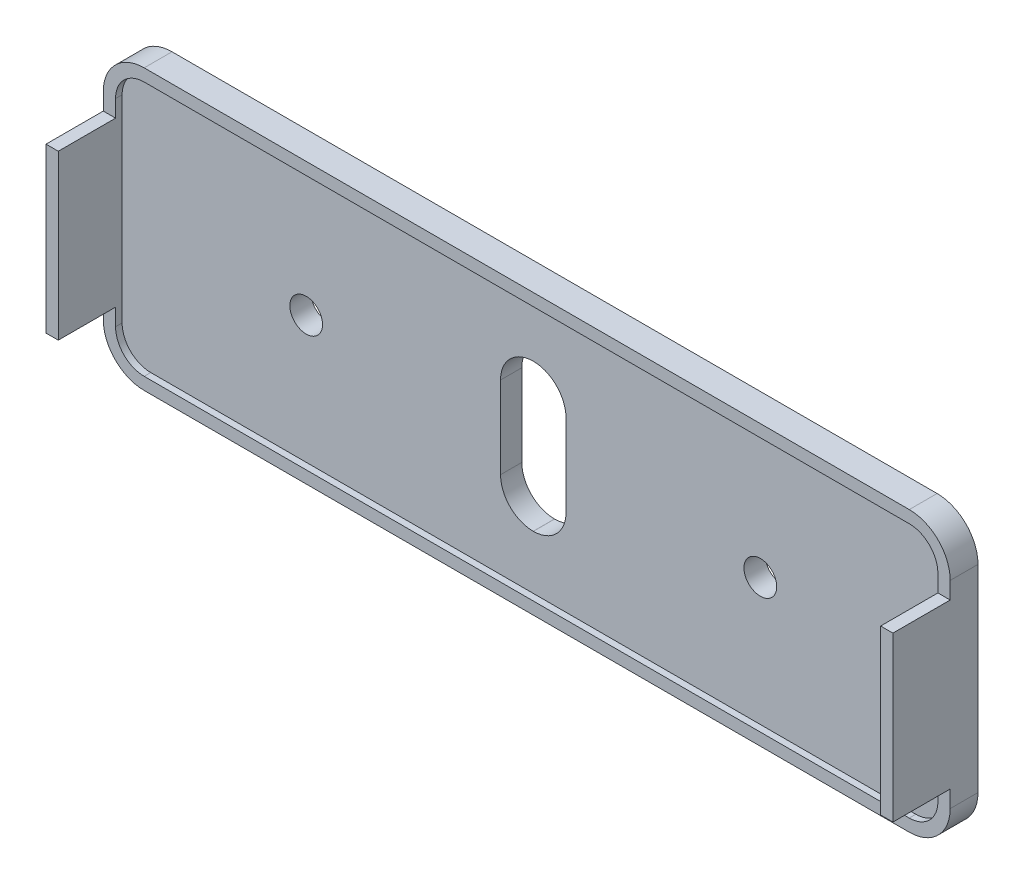
SolidWorks part; units mm, degrees
material "Custom Plastic"
ref_plane "X-Y Datum" through (0, 0, 0) normal (0, 0, 1) x (1, 0, 0)
ref_plane "X-Z Datum" through (0, 0, 0) normal (0, 1, 0) x (1, 0, 0)
ref_plane "Y-Z Datum" through (0, 0, 0) normal (1, 0, 0) x (0, 0, -1)
sketch "Sketch1" plane through (0, 0, 0) normal (0, 0, 1) x (1, 0, 0)
  line L0 (-27.75, 0) -> (27.75, 0) construction
  line L1 (-46.75, 17.075) -> (46.75, 17.075)
  line L2 (-51.75, 12.075) -> (-51.75, -12.075)
  line L3 (-46.75, -17.075) -> (46.75, -17.075)
  line L4 (51.75, 12.075) -> (51.75, -12.075)
  line L5 (-51.75, 17.075) -> (51.75, -17.075) construction
  line L6 (-51.75, -17.075) -> (51.75, 17.075) construction
  line L8 (-0.01, 9) -> (0.01, 9)
  line L9 (-4, 5.01) -> (-4, -5.01)
  line L10 (-0.01, -9) -> (0.01, -9)
  line L11 (4, 5.01) -> (4, -5.01)
  line L12 (-4, 9) -> (4, -9) construction
  line L13 (-4, -9) -> (4, 9) construction
  circle A0 centre (-27.75, 0) radius 2
  circle A1 centre (27.75, 0) radius 2
  arc A2 (0.01, -9) -> (4, -5.01) centre (0.01, -5.01) ccw
  arc A3 (-4, -5.01) -> (-0.01, -9) centre (-0.01, -5.01) ccw
  arc A4 (0.01, 9) -> (4, 5.01) centre (0.01, 5.01) cw
  arc A5 (-0.01, 9) -> (-4, 5.01) centre (-0.01, 5.01) ccw
  arc A6 (-46.75, 17.075) -> (-51.75, 12.075) centre (-46.75, 12.075) ccw
  arc A7 (-51.75, -12.075) -> (-46.75, -17.075) centre (-46.75, -12.075) ccw
  arc A8 (46.75, -17.075) -> (51.75, -12.075) centre (46.75, -12.075) ccw
  arc A9 (46.75, 17.075) -> (51.75, 12.075) centre (46.75, 12.075) cw
  point P0 (0, 0)
  point P9 (0, 0)
  point P11 (0, 0)
  dimension "D4" = 4
  dimension "D7" = 3.99
  dimension "D8" = 5
  dimension "D1" = 34.15
  dimension "D2" = 103.5
  dimension "D3" = 55.5
  dimension "D5" = 8
  dimension "D6" = 18
extrude "Boss-Extrude1" add sketch "Sketch1" along normal blind 3.4
sketch "Sketch2" plane through (0, 0, 3.4) normal (0, 0, 1) x (1, 0, 0)
  line L0 (-50.25, 12.075) -> (-50.25, -12.075)
  line L1 (-46.75, -15.575) -> (46.75, -15.575)
  line L2 (50.25, -12.075) -> (50.25, 12.075)
  line L3 (46.75, 15.575) -> (-46.75, 15.575)
  line L4 (-51.75, 12.075) -> (-51.75, -12.075)
  line L5 (-46.75, -17.075) -> (46.75, -17.075)
  line L6 (51.75, -12.075) -> (51.75, 12.075)
  line L7 (46.75, 17.075) -> (-46.75, 17.075)
  line L8 (-51.75, 12.075) -> (-51.75, -12.075)
  line L9 (-46.75, -17.075) -> (46.75, -17.075)
  line L10 (51.75, -12.075) -> (51.75, 12.075)
  line L11 (46.75, 17.075) -> (-46.75, 17.075)
  arc A0 (-46.75, 15.575) -> (-50.25, 12.075) centre (-46.75, 12.075) ccw
  arc A1 (-50.25, -12.075) -> (-46.75, -15.575) centre (-46.75, -12.075) ccw
  arc A2 (46.75, -15.575) -> (50.25, -12.075) centre (46.75, -12.075) ccw
  arc A3 (50.25, 12.075) -> (46.75, 15.575) centre (46.75, 12.075) ccw
  arc A4 (-46.75, 17.075) -> (-51.75, 12.075) centre (-46.75, 12.075) ccw
  arc A5 (-51.75, -12.075) -> (-46.75, -17.075) centre (-46.75, -12.075) ccw
  arc A6 (46.75, -17.075) -> (51.75, -12.075) centre (46.75, -12.075) ccw
  arc A7 (51.75, 12.075) -> (46.75, 17.075) centre (46.75, 12.075) ccw
  arc A8 (-46.75, 17.075) -> (-51.75, 12.075) centre (-46.75, 12.075) ccw
  arc A9 (-51.75, -12.075) -> (-46.75, -17.075) centre (-46.75, -12.075) ccw
  arc A10 (46.75, -17.075) -> (51.75, -12.075) centre (46.75, -12.075) ccw
  arc A11 (51.75, 12.075) -> (46.75, 17.075) centre (46.75, 12.075) ccw
  circle M17 centre (-27.75, 0) radius 2
  circle M26 centre (27.75, 0) radius 2
  line M27 (4, 5.01) -> (4, -5.01)
  arc M28 (4, -5.01) -> (0.01, -9) centre (0.01, -5.01) cw
  line M29 (0.01, -9) -> (-0.01, -9)
  arc M30 (-0.01, -9) -> (-4, -5.01) centre (-0.01, -5.01) cw
  line M31 (-4, -5.01) -> (-4, 5.01)
  arc M32 (-4, 5.01) -> (-0.01, 9) centre (-0.01, 5.01) cw
  line M33 (-0.01, 9) -> (0.01, 9)
  arc M34 (0.01, 9) -> (4, 5.01) centre (0.01, 5.01) cw
  dimension "D1" = 0
  dimension "D2" = 1.5
extrude "Cut-Extrude1" cut sketch "Sketch2" against normal blind 0.8 contours L2 A3 L3 A0 L0 A1 L1 A2 M17 M26 M34 M27 M28 M29 M30 M31 M32 M33
sketch "Sketch3" plane through (0, 0, 3.4) normal (0, 0, 1) x (1, 0, 0)
  line L0 (-50.25, 0) -> (-51.75, 0) construction
  line L1 (-50.25, 12.075) -> (-50.25, -12.075) construction
  line L2 (-51.75, 12.075) -> (-51.75, -12.075) construction
  line L3 (-50.25, 12.075) -> (-50.25, -12.075) construction
  line L4 (-51.75, 10) -> (-50.25, 10)
  line L5 (-51.75, 10) -> (-51.75, -10)
  line L6 (-51.75, -10) -> (-50.25, -10)
  line L7 (-50.25, 10) -> (-50.25, -10)
  line L8 (-51.75, 10) -> (-50.25, -10) construction
  line L9 (-51.75, -10) -> (-50.25, 10) construction
  point P6 (-51, 0)
  dimension "D1" = 20
extrude "Boss-Extrude2" add sketch "Sketch3" along normal blind 7
mirror "Mirror1" about plane through (0, 0, 0) normal (1, 0, 0) of "Boss-Extrude2"
